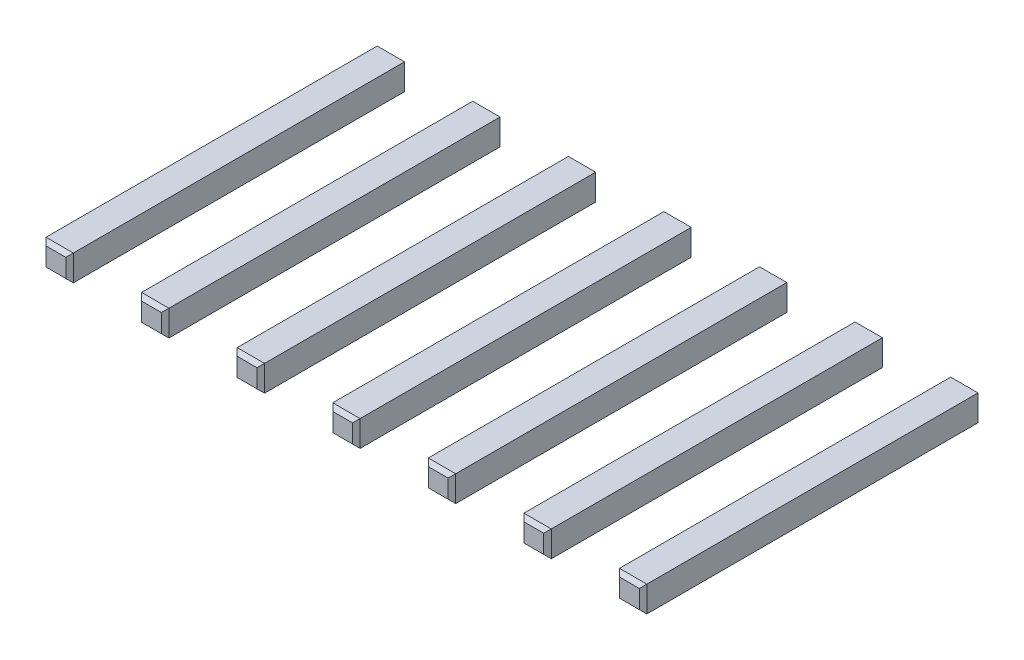
SolidWorks part; units mm, degrees
ref_plane "前视基准面" through (0, 0, 0) normal (0, 0, 1) x (1, 0, 0)
ref_plane "上视基准面" through (0, 0, 0) normal (0, 1, 0) x (1, 0, 0)
ref_plane "右视基准面" through (0, 0, 0) normal (1, 0, 0) x (0, 0, -1)
sketch "草图1" plane through (0, 0, 0) normal (0, 0, 1) x (1, 0, 0)
  line L0 (2.1768, 0.3437) -> (2.9032, 0.3437)
  line L1 (-0.3632, 0.3437) -> (0.3632, 0.3437)
  line L2 (-0.3632, 0.3437) -> (-0.3632, -0.3437)
  line L3 (-0.3632, -0.3437) -> (0.3632, -0.3437)
  line L4 (0.3632, 0.3437) -> (0.3632, -0.3437)
  line L5 (-0.3632, 0.3437) -> (0.3632, -0.3437) construction
  line L6 (-0.3632, -0.3437) -> (0.3632, 0.3437) construction
  line L7 (2.1768, 0.3437) -> (2.1768, -0.3437)
  line L8 (2.1768, -0.3437) -> (2.9032, -0.3437)
  line L9 (2.9032, 0.3437) -> (2.9032, -0.3437)
  line L10 (2.1768, 0.3437) -> (2.9032, -0.3437) construction
  line L11 (2.1768, -0.3437) -> (2.9032, 0.3437) construction
  line L12 (4.7168, 0.3437) -> (5.4432, 0.3437)
  line L13 (4.7168, 0.3437) -> (4.7168, -0.3437)
  line L14 (4.7168, -0.3437) -> (5.4432, -0.3437)
  line L15 (5.4432, 0.3437) -> (5.4432, -0.3437)
  line L16 (4.7168, 0.3437) -> (5.4432, -0.3437) construction
  line L17 (4.7168, -0.3437) -> (5.4432, 0.3437) construction
  line L18 (7.2568, 0.3437) -> (7.9832, 0.3437)
  line L19 (7.2568, 0.3437) -> (7.2568, -0.3437)
  line L20 (7.2568, -0.3437) -> (7.9832, -0.3437)
  line L21 (7.9832, 0.3437) -> (7.9832, -0.3437)
  line L22 (7.2568, 0.3437) -> (7.9832, -0.3437) construction
  line L23 (7.2568, -0.3437) -> (7.9832, 0.3437) construction
  line L24 (9.7968, 0.3437) -> (10.5232, 0.3437)
  line L25 (9.7968, 0.3437) -> (9.7968, -0.3437)
  line L26 (9.7968, -0.3437) -> (10.5232, -0.3437)
  line L27 (10.5232, 0.3437) -> (10.5232, -0.3437)
  line L28 (9.7968, 0.3437) -> (10.5232, -0.3437) construction
  line L29 (9.7968, -0.3437) -> (10.5232, 0.3437) construction
  line L30 (12.3368, 0.3437) -> (13.0632, 0.3437)
  line L31 (12.3368, 0.3437) -> (12.3368, -0.3437)
  line L32 (12.3368, -0.3437) -> (13.0632, -0.3437)
  line L33 (13.0632, 0.3437) -> (13.0632, -0.3437)
  line L34 (12.3368, 0.3437) -> (13.0632, -0.3437) construction
  line L35 (12.3368, -0.3437) -> (13.0632, 0.3437) construction
  line L36 (14.8768, 0.3437) -> (15.6032, 0.3437)
  line L37 (14.8768, 0.3437) -> (14.8768, -0.3437)
  line L38 (14.8768, -0.3437) -> (15.6032, -0.3437)
  line L39 (15.6032, 0.3437) -> (15.6032, -0.3437)
  line L40 (14.8768, 0.3437) -> (15.6032, -0.3437) construction
  line L41 (14.8768, -0.3437) -> (15.6032, 0.3437) construction
  circle A0 centre (0, 0) radius 0.5 construction
  circle A1 centre (2.54, 0) radius 0.5 construction
  circle A2 centre (5.08, 0) radius 0.5 construction
  circle A3 centre (7.62, 0) radius 0.5 construction
  circle A4 centre (10.16, 0) radius 0.5 construction
  circle A5 centre (12.7, 0) radius 0.5 construction
  circle A6 centre (15.24, 0) radius 0.5 construction
  dimension "D1" = 7
extrude "凸台-拉伸1" add sketch "草图1" along normal blind 9
chamfer "倒角1" distance 0.1 angle 45 4 edges at (15.24, 0.3437, 0) (14.8768, 0, 0) (15.24, -0.3437, 0) (15.6032, 0, 0)
chamfer "倒角2" distance 0.1 angle 45 4 edges at (12.7, 0.3437, 0) (12.3368, 0, 0) (12.7, -0.3437, 0) (13.0632, 0, 0)
chamfer "倒角3" distance 0.1 angle 45 4 edges at (10.16, 0.3437, 0) (9.7968, 0, 0) (10.16, -0.3437, 0) (10.5232, 0, 0)
chamfer "倒角4" distance 0.1 angle 45 4 edges at (7.62, 0.3437, 0) (7.2568, 0, 0) (7.62, -0.3437, 0) (7.9832, 0, 0)
chamfer "倒角5" distance 0.1 angle 45 4 edges at (5.08, 0.3437, 0) (4.7168, 0, 0) (5.08, -0.3437, 0) (5.4432, 0, 0)
chamfer "倒角6" distance 0.1 angle 45 4 edges at (2.54, 0.3437, 0) (2.1768, 0, 0) (2.54, -0.3437, 0) (2.9032, 0, 0)
chamfer "倒角7" distance 0.1 angle 45 4 edges at (0, 0.3437, 0) (-0.3632, 0, 0) (0, -0.3437, 0) (0.3632, 0, 0)
chamfer "倒角8" distance 0.1 angle 45 4 edges at (15.24, -0.3437, 9) (14.8768, 0, 9) (15.24, 0.3437, 9) (15.6032, 0, 9)
chamfer "倒角9" distance 0.1 angle 45 4 edges at (12.7, -0.3437, 9) (12.3368, 0, 9) (12.7, 0.3437, 9) (13.0632, 0, 9)
chamfer "倒角10" distance 0.1 angle 45 4 edges at (10.16, -0.3437, 9) (9.7968, 0, 9) (10.16, 0.3437, 9) (10.5232, 0, 9)
chamfer "倒角11" distance 0.1 angle 45 4 edges at (7.62, -0.3437, 9) (7.2568, 0, 9) (7.62, 0.3437, 9) (7.9832, 0, 9)
chamfer "倒角12" distance 0.1 angle 45 4 edges at (5.08, -0.3437, 9) (4.7168, 0, 9) (5.08, 0.3437, 9) (5.4432, 0, 9)
chamfer "倒角13" distance 0.1 angle 45 4 edges at (2.54, -0.3437, 9) (2.1768, 0, 9) (2.54, 0.3437, 9) (2.9032, 0, 9)
chamfer "倒角14" distance 0.1 angle 45 4 edges at (0, -0.3437, 9) (-0.3632, 0, 9) (0, 0.3437, 9) (0.3632, 0, 9)
